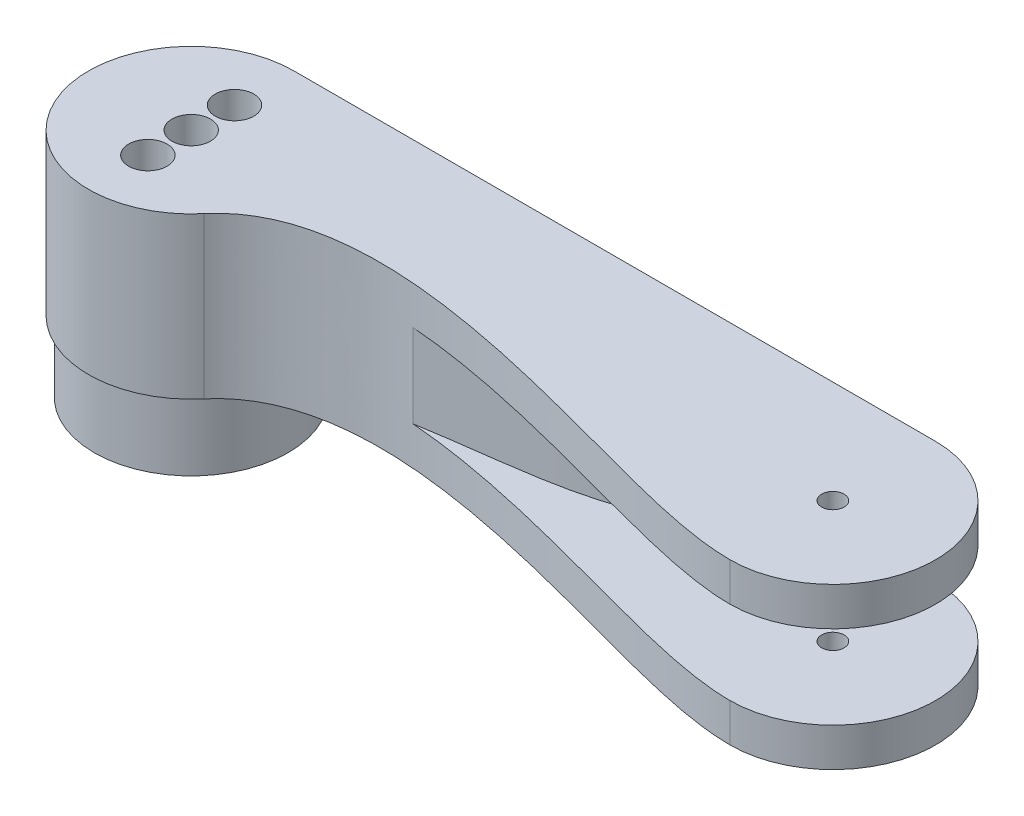
SolidWorks part; units mm, degrees
material "PLA"
ref_plane "Front Plane" through (0, 0, 0) normal (0, 0, 1) x (1, 0, 0)
ref_plane "Top Plane" through (0, 0, 0) normal (0, 1, 0) x (1, 0, 0)
ref_plane "Right Plane" through (0, 0, 0) normal (1, 0, 0) x (0, 0, -1)
sketch "Sketch1" plane through (0, 0, 0) normal (0, 1, 0) x (1, 0, 0)
  line L0 (-50, 0) -> (50, 0) construction
  line L1 (-50, 16) -> (50, 16)
  line L2 (-50, -16) -> (50, -16)
  arc A0 (-50, 16) -> (-50, -16) centre (-50, 0) ccw
  arc A1 (50, -16) -> (50, 16) centre (50, 0) ccw
  point P3 (0, 0)
  dimension "D1" = 16
  dimension "D2" = 100
extrude "Boss-Extrude1" add sketch "Sketch1" along normal blind 6
sketch "Sketch3" plane through (0, 0, 0) normal (0, -1, 0) x (1, 0, 0)
  circle A0 centre (50, 0) radius 1.75
  dimension "D1" = 3.5
extrude "Cut-Extrude2" cut sketch "Sketch3" against normal through all
sketch "Sketch4" plane through (0, 6, 0) normal (0, 1, 0) x (1, 0, 0)
  line L0 (-50, 16) -> (30, 16)
  line L1 (-50, 16) -> (50, 16) construction
  line L4 (-34.2857, -16) -> (-50, -16)
  line L5 (-50, -16) -> (50, -16) construction
  arc A0 (-50, 16) -> (-50, -16) centre (-50, 0) ccw
  arc A1 (-50, 16) -> (-50, -16) centre (-50, 0) ccw construction
  spline S0 degree 3 poles (30, 16) (21.9929, -10.8622) (-23.6763, 6.1181) (-34.2857, -16) knots 0 0 0 0 1 1 1 1
  dimension "D1" = 80
extrude "Boss-Extrude2" add sketch "Sketch4" along normal blind 13
sketch "Sketch5" plane through (0, 19, 0) normal (0, 1, 0) x (1, 0, 0)
  line L0 (-50, 0) -> (50, 0) construction
  line L1 (-50, 16) -> (50, 16)
  line L2 (-50, -16) -> (50, -16)
  arc A0 (-50, 16) -> (-50, -16) centre (-50, 0) ccw
  arc A1 (50, -16) -> (50, 16) centre (50, 0) ccw
  point P4 (0, 0)
  dimension "D1" = 16
extrude "Boss-Extrude3" add sketch "Sketch5" along normal blind 6
sketch "Sketch6" plane through (0, 25, 0) normal (0, 1, 0) x (1, 0, 0)
  circle A0 centre (50, 0) radius 1.75
  dimension "D1" = 3.5
extrude "Cut-Extrude3" cut sketch "Sketch6" against normal up to next
sketch "Sketch7" plane through (0, 25, 0) normal (0, 1, 0) x (1, 0, 0)
  line L0 (0, -3.3) -> (0, 3.3) construction
  line L1 (-50, -16) -> (50, -16)
  circle A0 centre (-50, 0) radius 16
  circle A1 centre (50, 0) radius 16
  spline S0 degree 3 poles (-37.7313, -10.2703) (-30.3326, -1.4318) (6.0504, -3.3646) (38.5122, -16) (50, -16) knots 0 0 0 0 0.426661 1 1 1 1
  line M5 (-50, -16) -> (50, -16)
extrude "Cut-Extrude4" cut sketch "Sketch7" against normal up to next contours S0 A0 M5
sketch "Sketch8" plane through (0, 0, 0) normal (0, -1, 0) x (1, 0, 0)
  circle A1 centre (-50, 0) radius 15.1
  dimension "D1" = 30.2
extrude "Boss-Extrude4" add sketch "Sketch8" along normal blind 11
sketch "Sketch9" plane through (0, -11, 0) normal (0, -1, 0) x (1, 0, 0)
  circle A0 centre (-50, 0) radius 6.75 construction
  circle A1 centre (-50, 6.75) radius 1.75
  circle A2 centre (-50, -6.75) radius 1.75
  arc A3 (-50, 16) -> (-50, -16) centre (-50, 0) ccw construction
  point P6 (-50, 0)
  dimension "D1" = 13.5
  dimension "D2" = 3.5
extrude "Cut-Extrude5" cut sketch "Sketch9" against normal blind 10
sketch "Sketch11" plane through (0, -11, 0) normal (0, -1, 0) x (1, 0, 0)
  circle A0 centre (-50, 0) radius 3
  dimension "D1" = 6
extrude "Cut-Extrude6" cut sketch "Sketch11" against normal up to next and the other way through all
sketch "Sketch12" plane through (0, -1, 0) normal (0, -1, 0) x (1, 0, 0)
  circle A0 centre (-50, 0) radius 6.75 construction
  circle A1 centre (-50, 6.75) radius 3
  circle A2 centre (-50, -6.75) radius 3
  circle A3 centre (-50, 6.75) radius 1.75 construction
  dimension "D1" = 6
  dimension "D3" = 13.5
  dimension "D2" = 2
extrude "Cut-Extrude7" cut sketch "Sketch12" against normal up to next
equation "\"Length\"= 100mm"
equation "\"Radius\"= 14.25mm"
equation "\"Thick\"= 12mm"
equation "\"D1@Sketch1\"=16"
equation "\"D2@Sketch1\" = \"Length\""
equation "\"D1@Boss-Extrude1\"= \"Thick\""
equation "\"D1@Sketch4\"=\"Length\"*0.8"
equation "\"D1@Sketch5\"=16"
equation "\"D1@Boss-Extrude4\"=\"Thick\"-1"
